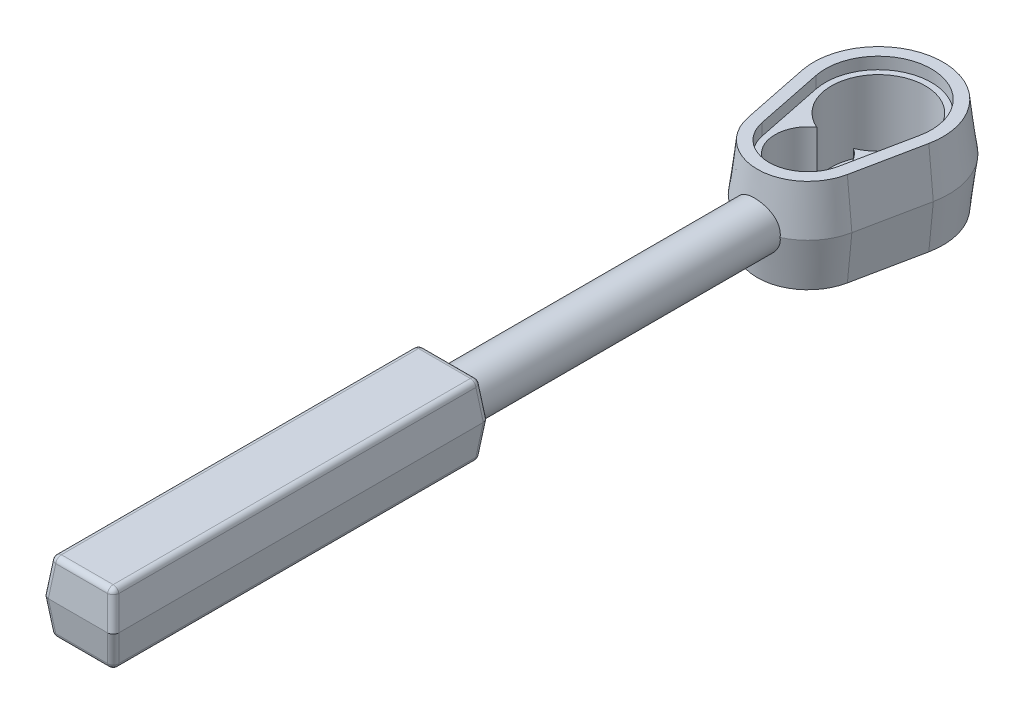
SolidWorks part; units mm, degrees
other "Markup1"
sketch "Sketch8"
ref_plane "Front Plane" through (0, 0, 0) normal (0, 0, 1) x (1, 0, 0)
ref_plane "Top Plane" through (0, 0, 0) normal (0, 1, 0) x (1, 0, 0)
ref_plane "Right Plane" through (0, 0, 0) normal (1, 0, 0) x (0, 0, -1)
sketch "Sketch1" plane through (0, 0, 0) normal (0, 1, 0) x (1, 0, 0)
  line L0 (0, -22.2975) -> (0, 26.407) construction
  line L1 (-14.9321, -6.32) -> (-18.6651, 11.968)
  line L2 (14.9321, -6.32) -> (18.6651, 11.968)
  arc A0 (-18.6651, 11.968) -> (18.6651, 11.968) centre (0, 15.778) cw
  arc A1 (-14.9321, -6.32) -> (14.9321, -6.32) centre (0, -3.272) ccw
  dimension "D1" = 19.05
  dimension "D2" = 15.24
  dimension "D3" = 19.05
extrude "Boss-Extrude1" add sketch "Sketch1" along normal mid plane 25.4 draft 7
sketch "Sketch2" plane through (0, 12.7, 0) normal (0, 1, 0) x (1, 0, 0)
  line L4 (10.2934, -5.3731) -> (14.0264, 12.9149)
  line L5 (-14.0264, 12.9149) -> (-10.2934, -5.3731)
  line L6 (10.2934, -5.3731) -> (14.0264, 12.9149)
  line L7 (-14.0264, 12.9149) -> (-10.2934, -5.3731)
  arc A7 (-10.2934, -5.3731) -> (10.2934, -5.3731) centre (0, -3.272) ccw
  arc A8 (14.0264, 12.9149) -> (-14.0264, 12.9149) centre (0, 15.778) ccw
  arc A9 (-10.2934, -5.3731) -> (10.2934, -5.3731) centre (0, -3.272) ccw
  arc A10 (14.0264, 12.9149) -> (-14.0264, 12.9149) centre (0, 15.778) ccw
  dimension "D2" = 3.175
extrude "Cut-Extrude1" cut sketch "Sketch2" against normal blind 3.175 contours A9 L6 A10 L7
sketch "Sketch3" plane through (0, 9.525, 0) normal (0, 1, 0) x (1, 0, 0)
  arc A0 (4.9774, 4.094) -> (-4.9774, 4.094) centre (0, 15.778) ccw
  arc A1 (-4.9774, 4.094) -> (4.9774, 4.094) centre (0, -3.272) ccw
  dimension "D1" = 25.4
  dimension "D2" = 17.78
extrude "Cut-Extrude2" cut sketch "Sketch3" against normal blind 19.05
sketch "Sketch4" plane through (0, -9.525, 0) normal (0, 1, 0) x (1, 0, 0)
  circle A0 centre (0, 15.778) radius 4.7625
  circle A1 centre (0, -3.272) radius 4.7625
  dimension "D1" = 9.525
  dimension "D2" = 9.525
extrude "Cut-Extrude3" cut sketch "Sketch4" against normal through all
ref_plane "Plane1" through (0, 0, 101.6) normal (0, 0, 1) x (1, 0, 0)
sketch "Sketch6" plane through (0, 0, 101.6) normal (0, 0, 1) x (1, 0, 0)
  circle A0 centre (0, 0) radius 6.35
  dimension "D1" = 12.7
extrude "Boss-Extrude2" add sketch "Sketch6" against normal up to next
sketch "Sketch7" plane through (0, 0, 0) normal (0, 1, 0) x (1, 0, 0)
  line L0 (0, 0) -> (0, -217.7446) construction
  line L1 (-9.525, -99.06) -> (9.525, -99.06)
  line L2 (-9.525, -99.06) -> (-9.525, -200.66)
  line L3 (-9.525, -200.66) -> (9.525, -200.66)
  line L4 (9.525, -99.06) -> (9.525, -200.66)
  line L5 (-9.525, -99.06) -> (9.525, -200.66) construction
  line L6 (-9.525, -200.66) -> (9.525, -99.06) construction
  point P0 (0, -149.86)
  point P8 (0, -131.3809)
  dimension "D1" = 101.6
  dimension "D2" = 19.05
  dimension "D3" = 99.06
extrude "Boss-Extrude3" add sketch "Sketch7" along normal mid plane 19.05 draft 7
fillet "Fillet1" radius 1.524 16 edges at (0, -9.525, 100.2295) (8.9402, -4.7625, 99.6448) (8.9402, 4.7625, 99.6448) (0, 9.525, 100.2295) (-8.9402, 4.7625, 99.6448) (-8.9402, -4.7625, 99.6448) (0, -9.525, 199.4905) (0, 9.525, 199.4905) (-8.9402, 4.7625, 200.0752) (-8.9402, -4.7625, 200.0752) (8.9402, 4.7625, 200.0752) (8.9402, -4.7625, 200.0752) (8.3555, -9.525, 149.86) (-8.3555, -9.525, 149.86) (-8.3555, 9.525, 149.86) (8.3555, 9.525, 149.86)
